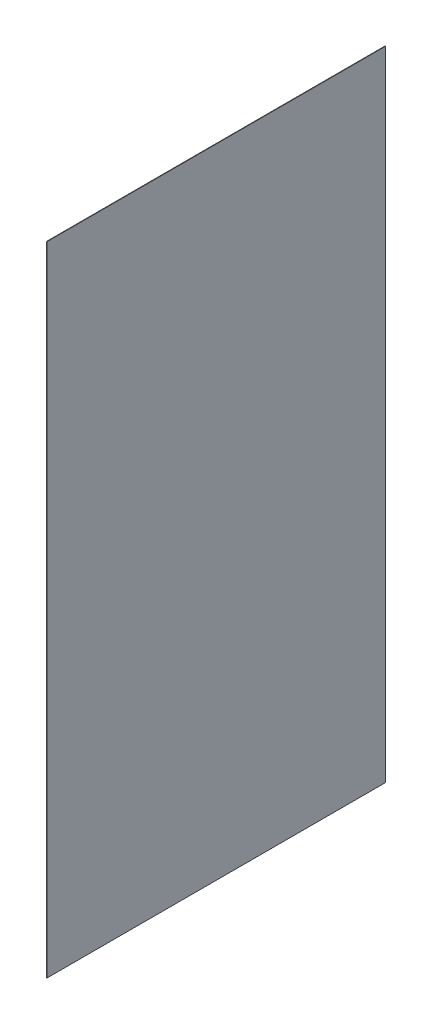
SolidWorks part; units mm, degrees
ref_plane "Front Plane" through (0, 0, 0) normal (0, 0, 1) x (1, 0, 0)
ref_plane "Top Plane" through (0, 0, 0) normal (0, 1, 0) x (1, 0, 0)
ref_plane "Right Plane" through (0, 0, 0) normal (1, 0, 0) x (0, 0, -1)
other "Configuration Table"
sketch "Sketch1" plane through (0, 0, 0) normal (0, 0, 1) x (1, 0, 0)
  line L1 (61.5, 181.5) -> (62.5, 181.5)
  line L2 (61.5, 181.5) -> (61.5, 1611)
  line L3 (61.5, 1611) -> (62.5, 1611)
  line L4 (62.5, 181.5) -> (62.5, 1611)
extrude "STORE_ic_yan_sol_1" add sketch "Sketch1" against normal blind 758.5 separate body
